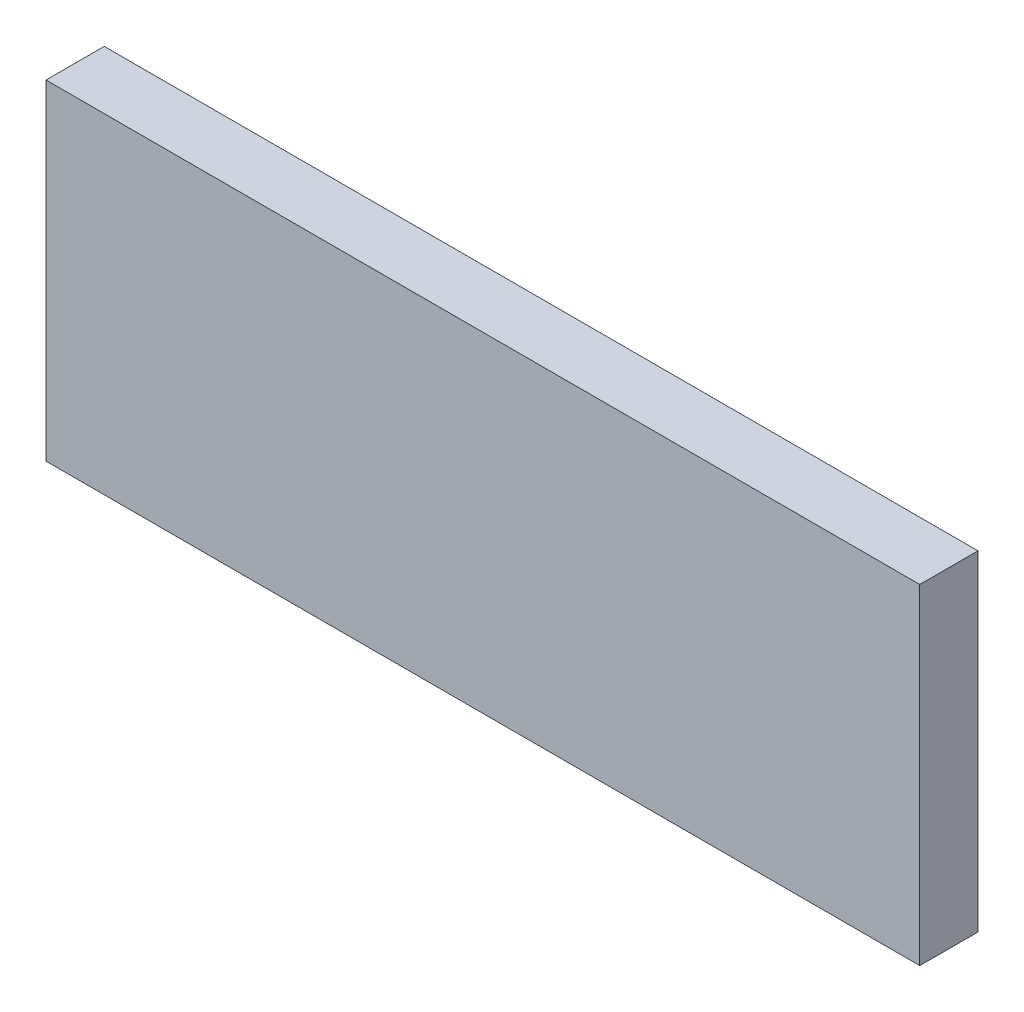
SolidWorks part; units mm, degrees
material "7050-T73510"
ref_plane "Front Plane" through (0, 0, 0) normal (0, 0, 1) x (1, 0, 0)
ref_plane "Top Plane" through (0, 0, 0) normal (0, 1, 0) x (1, 0, 0)
ref_plane "Right Plane" through (0, 0, 0) normal (1, 0, 0) x (0, 0, -1)
sketch "Sketch2" plane through (0, 0, 0) normal (0, 0, 1) x (1, 0, 0)
  line L1 (0, 0) -> (4500, 0)
  line L2 (0, 0) -> (0, 1700)
  line L3 (0, 1700) -> (4500, 1700)
  line L4 (4500, 0) -> (4500, 1700)
  dimension "Width" = 1700
  dimension "Length" = 4500
extrude "Boss-Extrude1" add sketch "Sketch2" along normal blind 300
shell "Shell1" thickness 10
